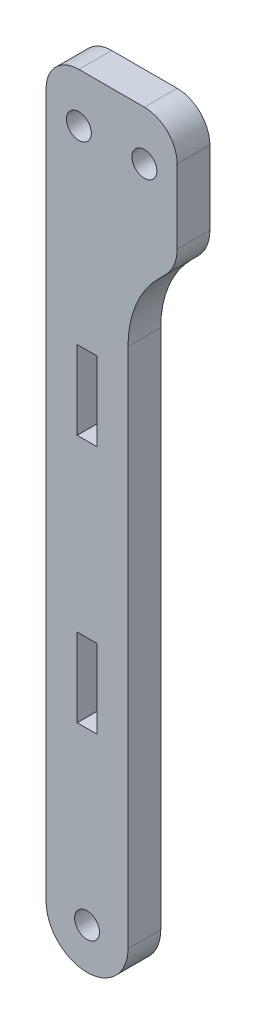
SolidWorks part; units mm, degrees
ref_plane "Plan de face" through (0, 0, 0) normal (0, 0, 1) x (1, 0, 0)
ref_plane "Plan de dessus" through (0, 0, 0) normal (0, 1, 0) x (1, 0, 0)
ref_plane "Plan de droite" through (0, 0, 0) normal (1, 0, 0) x (0, 0, -1)
sketch "Esquisse1" plane through (0, 0, 0) normal (0, 0, 1) x (1, 0, 0)
  line L0 (-7.2086, 11.4244) -> (-7.2086, 23.4244)
  line L1 (-7.2086, 23.4244) -> (-4.2086, 23.4244)
  line L2 (-4.2086, 23.4244) -> (-4.2086, 11.4244)
  line L3 (-7.2086, 11.4244) -> (-4.2086, 11.4244)
  line L4 (-5.7086, -52.5756) -> (-5.7086, -2.7616) construction
  line L5 (-6.9586, 59.9244) -> (3.0414, 59.9244)
  line L6 (-11.9586, -52.5756) -> (-11.9586, 54.9244)
  line L7 (0.5414, -52.5756) -> (0.5414, 27.047)
  line L8 (6.284, 39.4171) -> (5.2277, 38.3607)
  line L9 (8.0414, 54.9244) -> (8.0414, 43.6597)
  line L10 (-4.2086, -26.5756) -> (-7.2086, -26.5756)
  line L11 (-4.2086, -14.5756) -> (-7.2086, -14.5756)
  line L12 (-7.2086, -26.5756) -> (-7.2086, -14.5756)
  line L13 (-4.2086, -14.5756) -> (-4.2086, -26.5756)
  circle A0 centre (-5.7086, -52.5756) radius 1.9
  circle A1 centre (3.0414, 52.4244) radius 1.9
  circle A2 centre (-6.9586, 52.4244) radius 1.9
  arc A3 (8.0414, 54.9244) -> (3.0414, 59.9244) centre (3.0414, 54.9244) ccw
  arc A4 (-6.9586, 59.9244) -> (-11.9586, 54.9244) centre (-6.9586, 54.9244) ccw
  arc A5 (-11.9586, -52.5756) -> (0.5414, -52.5756) centre (-5.7086, -52.5756) ccw
  arc A7 (5.2277, 38.3607) -> (0.5414, 27.047) centre (16.5414, 27.047) ccw
  arc A8 (6.284, 39.4171) -> (8.0414, 43.6597) centre (2.0414, 43.6597) ccw
  dimension "D1" = 16
  dimension "D2" = 6
  dimension "D3" = 5
  dimension "D4" = 5
  dimension "D5" = 6.25
  dimension "D6" = 3.8
  dimension "D7" = 3.8
  dimension "D9" = 3.8
  dimension "D8" = 20
  dimension "D10" = 3
  dimension "D11" = 1.5
extrude "Boss.-Extru.1" add sketch "Esquisse1" along normal blind 5
